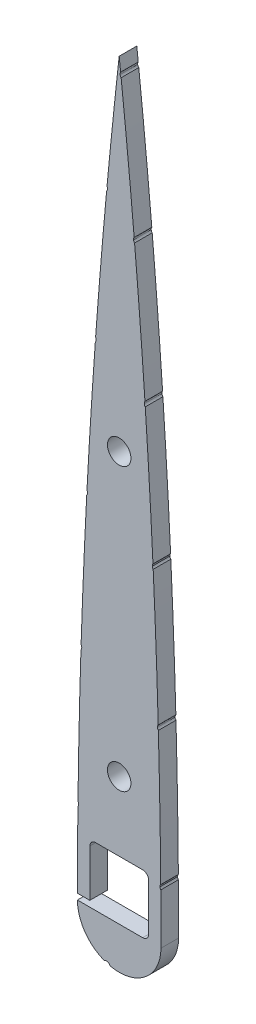
SolidWorks part; units mm, degrees
ref_plane "Front" through (0, 0, 0) normal (0, 0, 1) x (1, 0, 0)
ref_plane "Top" through (0, 0, 0) normal (0, 1, 0) x (1, 0, 0)
ref_plane "Right" through (0, 0, 0) normal (1, 0, 0) x (0, 0, -1)
sketch "Sketch1" plane through (0, 0, 0) normal (0, 0, 1) x (1, 0, 0)
  line L0 (24.2266, 498.2778) -> (16.2266, 498.2778) construction
  line L1 (25.2266, 489.2778) -> (25.2266, 497.2778) construction
  line L2 (16.2266, 488.2778) -> (24.2266, 488.2778) construction
  line L3 (15.2266, 497.2778) -> (15.2266, 489.2778) construction
  line L4 (24.2266, 498.2778) -> (16.2266, 498.2778)
  line L5 (25.2266, 489.2778) -> (25.2266, 497.2778)
  line L6 (16.2266, 488.2778) -> (24.2266, 488.2778)
  line L7 (15.2266, 497.2778) -> (15.2266, 489.2778)
  arc A0 (16.2266, 498.2778) -> (15.2266, 497.2778) centre (16.2266, 497.2778) ccw construction
  arc A1 (25.2266, 497.2778) -> (24.2266, 498.2778) centre (24.2266, 497.2778) ccw construction
  arc A2 (24.2266, 488.2778) -> (25.2266, 489.2778) centre (24.2266, 489.2778) ccw construction
  arc A3 (15.2266, 489.2778) -> (16.2266, 488.2778) centre (16.2266, 489.2778) ccw construction
  arc A4 (13.1214, 488.2778) -> (27.3319, 488.2778) centre (20.2266, 488.2778) ccw construction
  arc A5 (27.3319, 488.2778) -> (20.2266, 616.1726) centre (-1127.2734, 488.2778) ccw construction
  arc A6 (20.2266, 616.1726) -> (13.1214, 488.2778) centre (1167.7266, 488.2778) ccw construction
  arc A7 (16.2266, 498.2778) -> (15.2266, 497.2778) centre (16.2266, 497.2778) ccw
  arc A8 (25.2266, 497.2778) -> (24.2266, 498.2778) centre (24.2266, 497.2778) ccw
  arc A9 (24.2266, 488.2778) -> (25.2266, 489.2778) centre (24.2266, 489.2778) ccw
  arc A10 (15.2266, 489.2778) -> (16.2266, 488.2778) centre (16.2266, 489.2778) ccw
  arc A11 (13.1214, 488.2778) -> (27.3319, 488.2778) centre (20.2266, 488.2778) ccw
  arc A12 (27.3319, 488.2778) -> (20.2266, 616.1726) centre (-1127.2734, 488.2778) ccw
  arc A13 (20.2266, 616.1726) -> (13.1214, 488.2778) centre (1167.7266, 488.2778) ccw
extrude "Boss-Extrude1" add sketch "Sketch1" along normal blind 3
sketch "Sketch2" plane through (0, 0, 3) normal (0, 0, 1) x (1, 0, 0)
  text T0 " . . . . . . . . . . . ." font "Century Gothic" height in points 28
extrude "Cut-Extrude1" cut sketch "Sketch2" against normal blind 10
sketch "Sketch3" plane through (0, 0, 3) normal (0, 0, 1) x (1, 0, 0)
  line L0 (24.2266, 498.2778) -> (16.2266, 498.2778) construction
  line L1 (16.2266, 488.2778) -> (24.2266, 488.2778) construction
  line L2 (20.2266, 489.2778) -> (7.0002, 489.2778)
  line L3 (20.2266, 489.2778) -> (20.2266, 488.2778)
  line L4 (20.2266, 488.2778) -> (7.0002, 488.2778)
  line L5 (7.0002, 489.2778) -> (7.0002, 488.2778)
  circle A0 centre (20.2266, 510.0112) radius 2
  circle A1 centre (20.2266, 557.9197) radius 2
  point P7 (20.2266, 498.2778)
  dimension "D1" = 4
  dimension "D2" = 1
extrude "Cut-Extrude2" cut sketch "Sketch3" against normal blind 10
sketch "Sketch4" plane through (0, 0, 3) normal (0, 0, 1) x (1, 0, 0)
  line L0 (24.2266, 498.2778) -> (16.2266, 498.2778) construction
  line L1 (-4.7734, 475.3605) -> (45.2266, 475.3605)
  line L2 (-4.7734, 475.3605) -> (-4.7734, 626.1726)
  line L3 (-4.7734, 626.1726) -> (45.2266, 626.1726)
  line L4 (45.2266, 475.3605) -> (45.2266, 626.1726)
  point P6 (20.2266, 498.2778)
  point P7 (20.2266, 475.3605)
  point P8 (-4.7734, 475.3605)
  point P9 (-4.7734, 628.6386)
  dimension "D1" = 50
  dimension "D2" = 10
